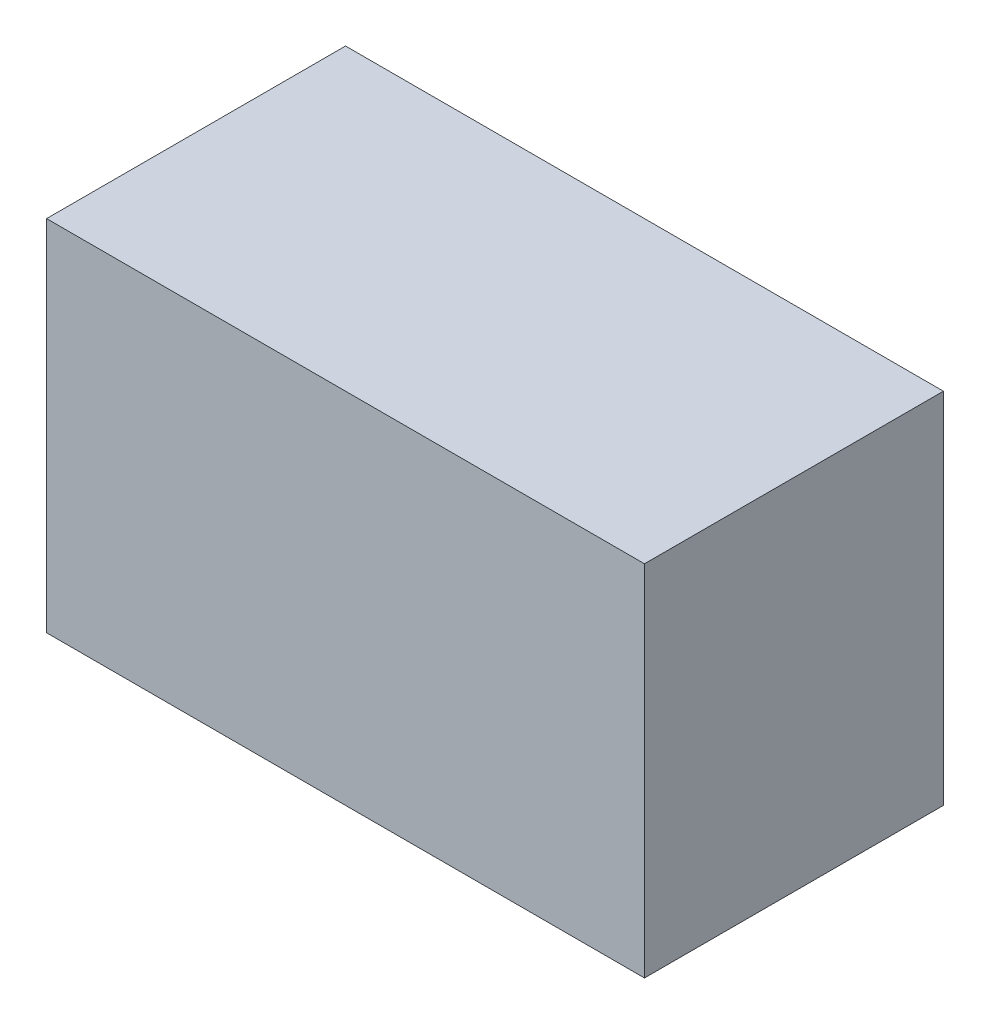
SolidWorks part; units mm, degrees
ref_plane "Front Plane" through (0, 0, 0) normal (0, 0, 1) x (1, 0, 0)
ref_plane "Top Plane" through (0, 0, 0) normal (0, 1, 0) x (1, 0, 0)
ref_plane "Right Plane" through (0, 0, 0) normal (1, 0, 0) x (0, 0, -1)
sketch "Sketch1" plane through (0, 0, 0) normal (0, 1, 0) x (1, 0, 0)
  line L1 (-15, -15) -> (15, -15)
  line L2 (-15, -15) -> (-15, 15)
  line L3 (-15, 15) -> (15, 15)
  line L4 (15, -15) -> (15, 15)
  line L5 (-15, -15) -> (15, 15) construction
  line L6 (-15, 15) -> (15, -15) construction
  point P0 (0, 0)
  dimension "D1" = 30
  dimension "D2" = 30
extrude "Boss-Extrude1" add sketch "Sketch1" along normal blind 18
sketch "Sketch2" plane through (0, 18, 0) normal (0, 1, 0) x (1, 0, 0)
  line L1 (15, -15) -> (0, -15)
  line L2 (15, -15) -> (15, 0)
  line L3 (15, 0) -> (0, 0)
  line L4 (0, -15) -> (0, 0)
extrude "Cut-Extrude1" cut sketch "Sketch2" against normal through all
sketch "Sketch3" plane through (0, 18, 0) normal (0, 1, 0) x (1, 0, 0)
  line L1 (-15, -15) -> (0, -15)
  line L2 (-15, -15) -> (-15, 0)
  line L3 (-15, 0) -> (0, 0)
  line L4 (0, -15) -> (0, 0)
extrude "Cut-Extrude2" cut sketch "Sketch3" against normal through all
